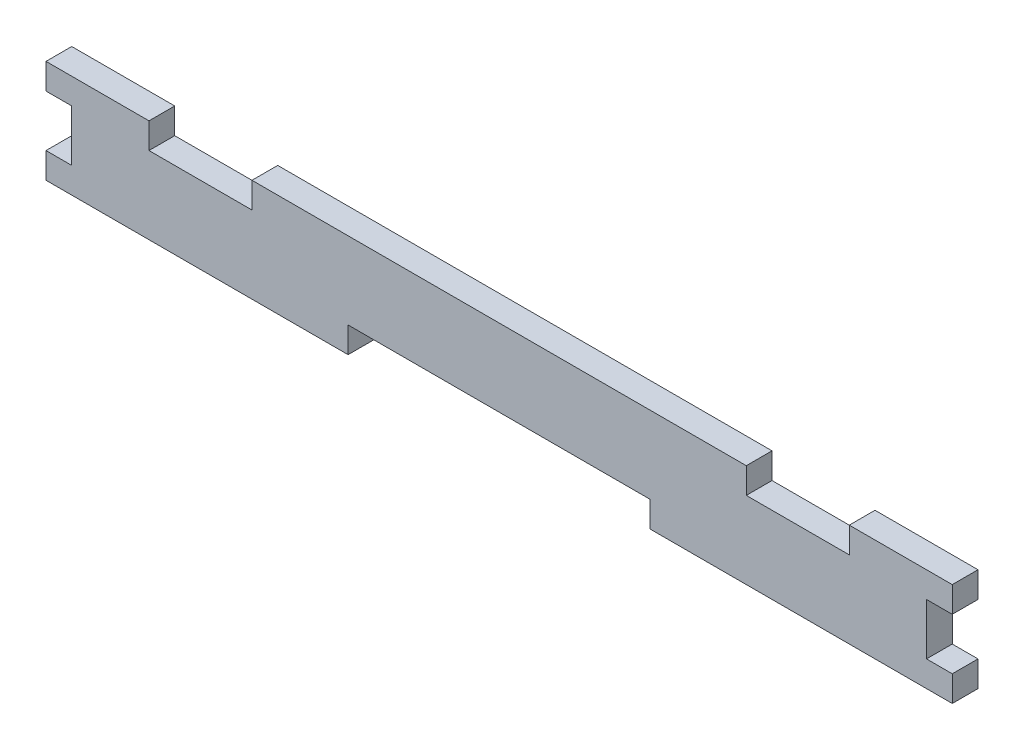
SolidWorks part; units mm, degrees
ref_plane "Alzado" through (0, 0, 0) normal (0, 0, 1) x (1, 0, 0)
ref_plane "Planta" through (0, 0, 0) normal (0, 1, 0) x (1, 0, 0)
ref_plane "Vista lateral" through (0, 0, 0) normal (1, 0, 0) x (0, 0, -1)
sketch "Croquis1" plane through (0, 0, 0) normal (0, 0, 1) x (1, 0, 0)
  line L0 (117.3333, 0) -> (176, 0)
  line L1 (0, 0) -> (58.6667, 0)
  line L2 (0, 0) -> (0, 5)
  line L3 (0, 20) -> (20, 20)
  line L4 (176, 0) -> (176, 5)
  line L6 (58.6667, 0) -> (58.6667, 5)
  line L7 (58.6667, 5) -> (117.3333, 5)
  line L8 (117.3333, 0) -> (117.3333, 5)
  line L9 (88, 15) -> (88, 10) construction
  line L10 (0, 15) -> (5, 15)
  line L12 (0, 5) -> (5, 5)
  line L13 (5, 15) -> (5, 5)
  line L14 (0, 15) -> (0, 20)
  line L15 (176, 15) -> (171, 15)
  line L16 (171, 15) -> (171, 5)
  line L17 (176, 5) -> (171, 5)
  line L18 (176, 15) -> (176, 20)
  line L19 (136, 20) -> (136, 15)
  line L25 (20, 20) -> (20, 15)
  line L26 (20, 15) -> (40, 15)
  line L27 (40, 20) -> (40, 15)
  line L28 (156, 15) -> (136, 15)
  line L29 (156, 20) -> (156, 15)
  line L30 (40, 20) -> (136, 20)
  line L31 (156, 20) -> (176, 20)
  dimension "D1" = 176
  dimension "D2" = 20
  dimension "D3" = 58.6667
  dimension "D4" = 58.6667
  dimension "D5" = 5
  dimension "D6" = 10
  dimension "D7" = 5
  dimension "D8" = 5
  dimension "D9" = 5
  dimension "D10" = 20
  dimension "D11" = 20
extrude "Saliente-Extruir1" add sketch "Croquis1" along normal blind 5
